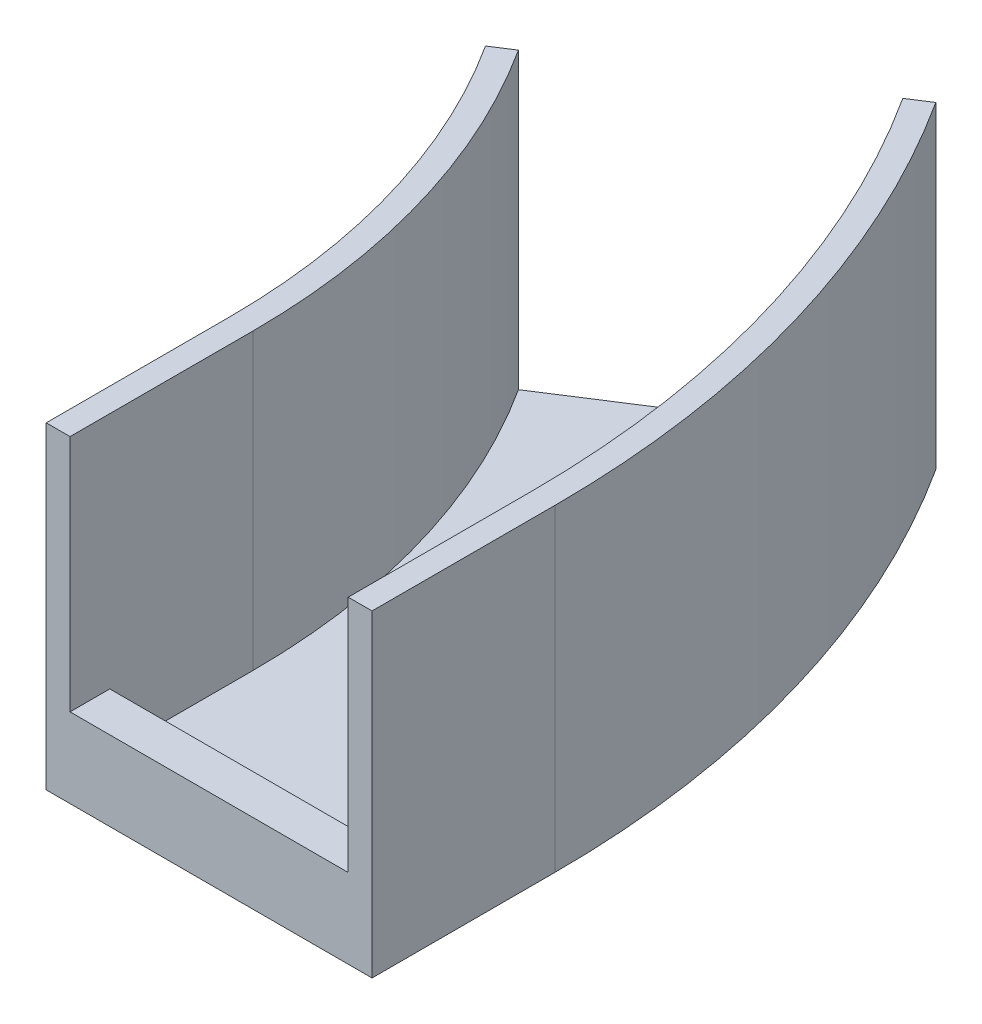
SolidWorks part; units mm, degrees
ref_plane "Front Plane" through (0, 0, 0) normal (0, 0, 1) x (1, 0, 0)
ref_plane "Top Plane" through (0, 0, 0) normal (0, 1, 0) x (1, 0, 0)
ref_plane "Right Plane" through (0, 0, 0) normal (1, 0, 0) x (0, 0, -1)
sketch "Sketch1" plane through (0, 0, 0) normal (0, 1, 0) x (1, 0, 0)
  line L0 (0, 0) -> (185.4514, 0) construction
  line L1 (0, 0) -> (87.5, 0)
  line L2 (0, 0) -> (73.5992, 47.3224)
  line L3 (0, 0) -> (122.5, 0)
  line L4 (0, 0) -> (103.0388, 66.2514)
  line L5 (87.5, 0) -> (87.5, -20)
  line L6 (122.5, 0) -> (122.5, -20)
  line L7 (87.5, -20) -> (87.5, -23)
  line L8 (107.1847, 65.3505) -> (107.1546, 65.3311)
  line L9 (87.5, -23) -> (84.5, -23)
  line L10 (84.5, 0) -> (84.5, -23)
  line L11 (71.0758, 45.6999) -> (73.5992, 47.3224)
  line L12 (122.5, -20) -> (122.5, -23)
  line L13 (125.5, 0) -> (125.5, -23)
  line L14 (125.5, -23) -> (84.5, -23) construction
  line L15 (122.5, -20) -> (87.5, -20) construction
  line L16 (105.5622, 67.8739) -> (103.0388, 66.2514)
  line L17 (125.5, -23) -> (122.5, -23)
  line L18 (125.5, 0) -> (125.5, -23) construction
  arc A0 (87.5, 0) -> (73.5992, 47.3224) centre (0, 0) ccw
  arc A1 (122.5, 0) -> (103.0388, 66.2514) centre (0, 0) ccw
  arc A2 (84.5, 0) -> (71.0758, 45.6999) centre (0, 0) ccw
  arc A4 (125.5, 0) -> (105.5622, 67.8739) centre (0, 0) ccw
  arc A5 (125.5, 0) -> (107.1546, 65.3311) centre (0, 0) ccw construction
  dimension "D4" = 122.5
  dimension "D1" = 87.5
  dimension "D2" = 87.5
  dimension "D3" = 32.74
  dimension "D5" = 122.5
  dimension "D6" = 32.74
  dimension "D7" = 20
  dimension "D8" = 3
  dimension "D9" = 3
extrude "Boss-Extrude1" add sketch "Sketch1" along normal blind 40 contours L5 L7 L9 L10 A2 L11 A0 | L6 L12 L17 L13 A4 L16 A1
sketch "Sketch2" plane through (0, 0, 0) normal (0, -1, 0) x (1, 0, 0)
  line L0 (87.5, 23) -> (122.5, 23)
  line L3 (87.4825, 18) -> (122.5, 18)
  line L6 (87.4825, 18) -> (87.5, 23)
  line L7 (122.5, 23) -> (122.5, 18)
  line L8 (122.5, 0) -> (122.5, 23) construction
extrude "Boss-Extrude2" add sketch "Sketch2" against normal blind 10
sketch "Sketch3" plane through (0, 0, 0) normal (0, -1, 0) x (1, 0, 0)
  line L0 (73.5992, -47.3224) -> (103.0388, -66.2514)
  line L8 (87.5, 0) -> (87.5, 18)
  line L9 (87.5, 18) -> (122.5, 18)
  line L10 (122.5, 18) -> (122.5, 0)
  line L11 (103.0388, -66.2514) -> (105.5622, -67.8739)
  line L12 (125.5, 0) -> (125.5, 23)
  line L13 (125.5, 23) -> (84.5, 23)
  line L14 (84.5, 23) -> (84.5, 0)
  line L15 (71.0758, -45.6999) -> (73.5992, -47.3224)
  line L16 (87.5, 0) -> (87.5, 18)
  line L17 (87.5, 18) -> (122.5, 18)
  line L18 (122.5, 18) -> (122.5, 0)
  line L19 (103.0388, -66.2514) -> (105.5622, -67.8739)
  line L20 (125.5, 0) -> (125.5, 23)
  line L21 (125.5, 23) -> (84.5, 23)
  line L22 (84.5, 23) -> (84.5, 0)
  line L23 (71.0758, -45.6999) -> (73.5992, -47.3224)
  arc A4 (103.0388, -66.2514) -> (122.5, 0) centre (0, 0) ccw
  arc A5 (105.5622, -67.8739) -> (125.5, 0) centre (0, 0) ccw
  arc A6 (71.0758, -45.6999) -> (84.5, 0) centre (0, 0) ccw
  arc A7 (73.5992, -47.3224) -> (87.5, 0) centre (0, 0) ccw
  arc A8 (103.0388, -66.2514) -> (122.5, 0) centre (0, 0) ccw
  arc A9 (105.5622, -67.8739) -> (125.5, 0) centre (0, 0) ccw
  arc A10 (71.0758, -45.6999) -> (84.5, 0) centre (0, 0) ccw
  arc A11 (73.5992, -47.3224) -> (87.5, 0) centre (0, 0) ccw
  line M13 (87.5, 0) -> (87.5, 18)
  line M14 (87.5, 18) -> (122.5, 18)
  line M15 (122.5, 18) -> (122.5, 0)
  arc M16 (122.5, 0) -> (103.0388, -66.2514) centre (0, 0) cw
  arc M24 (73.5992, -47.3224) -> (87.5, 0) centre (0, 0) ccw
  dimension "D1" = 0
extrude "Boss-Extrude3" add sketch "Sketch3" against normal blind 3 contours L0 M24 M16 M15 M14 M13
